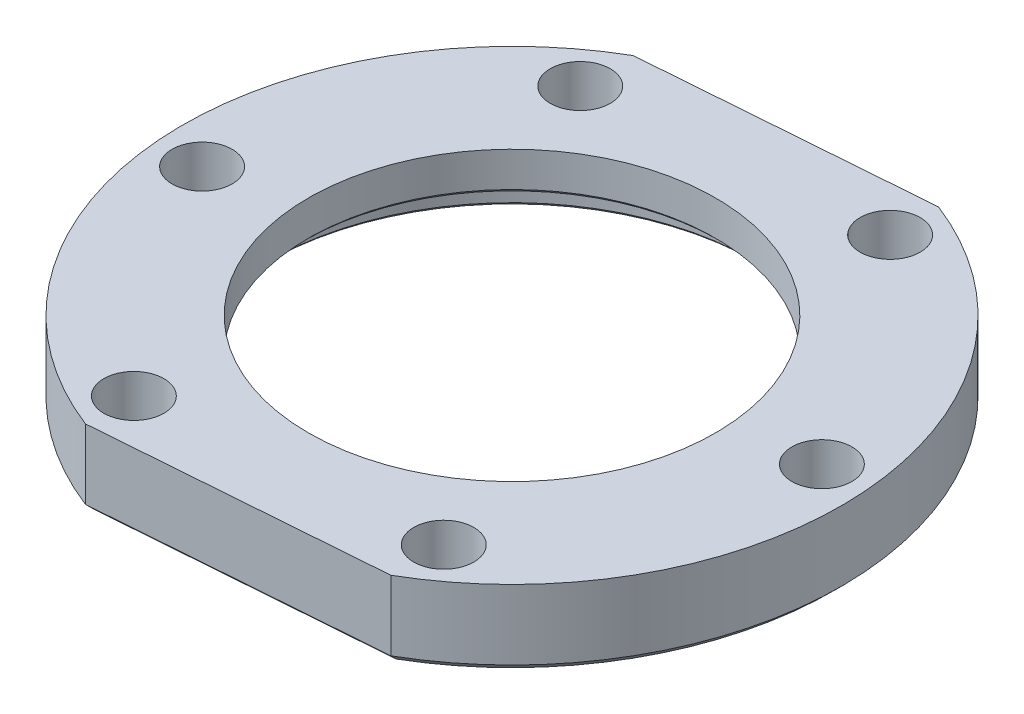
SolidWorks part; units mm, degrees
ref_plane "Front Plane" through (0, 0, 0) normal (0, 0, 1) x (1, 0, 0)
ref_plane "Top Plane" through (0, 0, 0) normal (0, 1, 0) x (1, 0, 0)
ref_plane "Right Plane" through (0, 0, 0) normal (1, 0, 0) x (0, 0, -1)
sketch "Sketch1" plane through (0, 0, 0) normal (0, 1, 0) x (1, 0, 0)
  circle A0 centre (0, 0) radius 17
  circle A1 centre (0, 0) radius 12.5
  dimension "D1" = 34
  dimension "D2" = 25
extrude "Boss-Extrude1" add sketch "Sketch1" along normal blind 4
sketch "Sketch2" plane through (0, 4, 0) normal (0, 1, 0) x (1, 0, 0)
  line L0 (-8.485, 14.7311) -> (6.1544, 15.8469)
  line L5 (-8.485, 26.5236) -> (0, 0) construction
  line L6 (0, 0) -> (8.485, 26.5236) construction
  line L7 (6.1544, 15.8469) -> (5.9457, 18.5858)
  line L8 (5.9457, 18.5858) -> (-8.485, 17.486)
  line L9 (-8.485, 17.486) -> (-8.485, 14.7311)
  line L10 (-7.0461, -0.537) -> (7.6149, 0.5804) construction
  line L11 (8.485, -14.7311) -> (8.6938, -17.4701)
  line L12 (8.6938, -17.4701) -> (-5.7369, -18.5699)
  line L13 (-5.7369, -18.5699) -> (-6.1544, -15.8469)
  line L14 (-6.1544, -15.8469) -> (8.485, -14.7311)
  circle A0 centre (-8.485, 12.0053) radius 1.55
  circle A3 centre (6.1544, 13.3509) radius 1.55
  circle A4 centre (14.6394, 1.3456) radius 1.55
  circle A5 centre (8.485, -12.0053) radius 1.55
  circle A6 centre (-6.1544, -13.3509) radius 1.55
  circle A7 centre (-14.6394, -1.3456) radius 1.55
  circle A9 centre (0, 0) radius 17 construction
  point P3 (0, 0)
  point P17 (0, 0)
  dimension "D1" = 3.1
  dimension "D2" = 6
extrude "Cut-Extrude1" cut sketch "Sketch2" against normal through all
sketch "Sketch3" plane through (0, 4, 0) normal (0, 1, 0) x (1, 0, 0)
  circle A0 centre (0, 0) radius 10.5
  circle A1 centre (0, 0) radius 12.5 construction
  circle A2 centre (0, 0) radius 12.5
  dimension "D1" = 21
extrude "Boss-Extrude2" add sketch "Sketch3" against normal blind 2
chamfer "Chamfer1" distance 0.2 angle 45 3 edges at (0, 2, 10.5) (0, 0, 12.5) (0, 2, 12.5)
chamfer "Chamfer2" distance 0.4 angle 45 4 edges at (1.1653, 0, 15.289) (-16.9508, 0, 1.2919) (16.9508, 0, -1.2919) (-1.1653, 0, -15.289)
